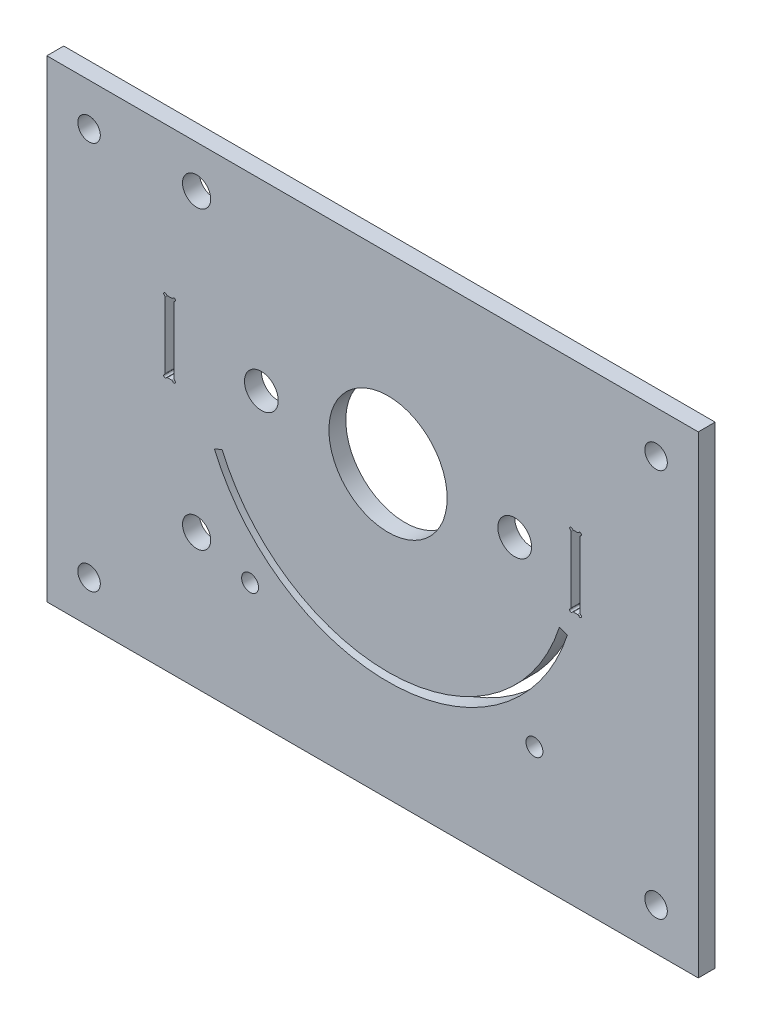
SolidWorks part; units mm, degrees
ref_plane "Front Plane" through (0, 0, 0) normal (0, 0, 1) x (1, 0, 0)
ref_plane "Top Plane" through (0, 0, 0) normal (0, 1, 0) x (1, 0, 0)
ref_plane "Right Plane" through (0, 0, 0) normal (1, 0, 0) x (0, 0, -1)
sketch "Sketch2" plane through (0, 0, 0) normal (0, 0, 1) x (1, 0, 0)
  line L12 (0, 0) -> (0, -103) construction
  line L13 (0, 50) -> (-68, 50) construction
  line L23 (0, 0) -> (0, 50) construction
  line L24 (0, 0) -> (-76, 0) construction
  line L25 (-76, -12.6) -> (-76, 12.6)
  line L26 (-76, 12.6) -> (-79.2, 12.6)
  line L27 (-79.2, 12.6) -> (-79.2, -12.6)
  line L28 (-79.2, -12.6) -> (-76, -12.6)
  line L29 (-68, 50) -> (-68, 65) construction
  line L30 (-79.2, 0) -> (-106.2, 0) construction
  line L31 (-106.2, 0) -> (-106.2, 50) construction
  line L33 (-68, 65) -> (95.2, 65)
  line L41 (0, 0) -> (60, 0) construction
  line L42 (60, 0) -> (65, 0) construction
  line L43 (65, -12.6) -> (65, 12.6)
  line L44 (65, 12.6) -> (68.2, 12.6)
  line L45 (68.2, 12.6) -> (68.2, -12.6)
  line L46 (65, -12.6) -> (68.2, -12.6)
  line L47 (68.2, 0) -> (95.2, 0) construction
  line L48 (95.2, 0) -> (95.2, 50) construction
  line L54 (-68, 50) -> (-68, -55) construction
  line L59 (95.2, 65) -> (110.2, 65)
  line L62 (0, -103) -> (110.2, -103)
  line L63 (110.2, 65) -> (110.2, -103)
  line L64 (-68, 65) -> (-106.2, 65)
  line L65 (-106.2, 65) -> (-121.2, 65)
  line L66 (-121.2, 65) -> (-121.2, -103)
  line L67 (0, -103) -> (-121.2, -103)
  circle A7 centre (0, 0) radius 21
  circle A8 centre (-68, 50) radius 5 construction
  circle A9 centre (-68, -55) radius 5 construction
  point P9 (-76, 0)
  point P13 (0, -103)
  point P25 (65, 0)
  dimension "D1" = 42
  dimension "D4" = 10
  dimension "D10" = 27
  dimension "D11" = 15
  dimension "D12" = 15
  dimension "D26" = 10
  dimension "D2" = 103
  dimension "D3" = 68
  dimension "D5" = 76
  dimension "D6" = 50
  dimension "D7" = 25.2
  dimension "D8" = 3.2
  dimension "D9" = 15
  dimension "D14" = 60
  dimension "D15" = 5
  dimension "D16" = 25.2
  dimension "D17" = 3.2
  dimension "D18" = 27
  dimension "D19" = 50
  dimension "D20" = 50
  dimension "D25" = 105
extrude "Boss-Extrude1" add sketch "Sketch2" along normal mid plane 6
sketch "Sketch6" plane through (0, 0, 0) normal (0, 0, 1) x (1, 0, 0)
  line L0 (-121.2, 65) -> (-106.2, 65) construction
  line L1 (110.2, 65) -> (-121.2, 65) construction
  line L2 (-106.2, 65) -> (-106.2, 50) construction
  line L3 (110.2, 65) -> (95.2, 65) construction
  line L4 (95.2, 65) -> (95.2, 50) construction
  line L5 (110.2, -103) -> (95.2, -103) construction
  line L6 (-121.2, -103) -> (110.2, -103) construction
  line L7 (95.2, -103) -> (95.2, -88) construction
  line L8 (-121.2, -103) -> (-106.2, -103) construction
  line L9 (-106.2, -103) -> (-106.2, -88) construction
  line L10 (-106.2, 50) -> (-68, 50) construction
  line L11 (-121.2, 65) -> (-121.2, -103) construction
  line L12 (-68, 50) -> (-68, -55) construction
  dimension "D1" = 15
  dimension "D2" = 15
  dimension "D3" = 15
  dimension "D4" = 15
  dimension "D5" = 15
  dimension "D6" = 15
  dimension "D7" = 15
  dimension "D8" = 15
  dimension "D9" = 53.2
  dimension "D10" = 105
hole_wizard "Ø10.0 (10) Diameter Hole1" positions "Sketch11" profile "Sketch12" hole size "Ø10.0" standard "AS" end condition through all
sketch "Sketch11" plane through (0, 0, 3) normal (0, 0, 1) x (1, 0, 0)
  point P0 (-68, 50)
  point P3 (-68, -55)
sketch "Sketch12" plane through (-68, 50, 3) normal (1, 0, 0) x (0, -1, 0)
  line L0 (0, 0) -> (0, 6)
  line L1 (0, 6) -> (5, 6)
  line L2 (5, 6) -> (5, 0)
  line L5 (5, 0) -> (0, 0)
  line L11 (0, -6.35) -> (0, 107.95) construction
  dimension "Thru Hole Dia." = 10
  dimension "Thru Hole Depth" = 6
hole_wizard "Ø8.0 (8) Diameter Hole1" positions "Sketch13" profile "Sketch14" hole size "Ø8.0" standard "AS" end condition through all
sketch "Sketch13" plane through (0, 0, 3) normal (0, 0, 1) x (1, 0, 0)
  point P0 (-106.2, 50)
  point P3 (-106.2, -88)
  point P6 (95.2, -88)
  point P9 (95.2, 50)
sketch "Sketch14" plane through (-106.2, 50, 3) normal (1, 0, 0) x (0, -1, 0)
  line L0 (0, 0) -> (0, 6)
  line L1 (0, 6) -> (4, 6)
  line L2 (4, 6) -> (4, 0)
  line L5 (4, 0) -> (0, 0)
  line L11 (0, -6.35) -> (0, 107.95) construction
  dimension "Thru Hole Dia." = 8
  dimension "Thru Hole Depth" = 6
sketch "Sketch15" plane through (0, 0, -3) normal (0, 0, -1) x (-1, 0, 0)
  line L0 (-45, 0) -> (45, 0) construction
  point P4 (0, 0)
  point P6 (-45, 0)
  point P7 (45, 0)
  dimension "D1" = 90
hole_wizard "Ø12.0 (12) Diameter Hole1" positions "Sketch16" profile "Sketch17" hole size "Ø12.0" standard "ANSI Metric" end condition through all
sketch "Sketch16" plane through (0, 0, -3) normal (0, 0, -1) x (-1, 0, 0)
  point P0 (-45, 0)
  point P3 (45, 0)
sketch "Sketch17" plane through (45, 0, -3) normal (1, 0, 0) x (0, 1, 0)
  line L0 (0, 0) -> (0, 6)
  line L1 (0, 6) -> (6, 6)
  line L2 (6, 6) -> (6, 0)
  line L5 (6, 0) -> (0, 0)
  line L11 (0, -6.35) -> (0, 107.95) construction
  dimension "Thru Hole Dia." = 12
  dimension "Thru Hole Depth" = 6
sketch "Sketch18" plane through (0, 0, 3) normal (0, 0, 1) x (1, 0, 0)
  line L0 (0, 0) -> (0, -147.0901) construction
  line L1 (-58.9123, -25.0068) -> (-61.6738, -26.179)
  line L2 (60.8676, -19.7771) -> (63.7208, -20.7041)
  arc A1 (-61.6738, -26.179) -> (63.7208, -20.7041) centre (0, 0) ccw
  arc A2 (-58.9123, -25.0068) -> (60.8676, -19.7771) centre (0, 0) ccw
  dimension "D1" = 134
  dimension "D2" = 3
  dimension "D3" = 67
  dimension "D4" = 72
extrude "Cut-Extrude1" cut sketch "Sketch18" against normal through all both and the other way through all
sketch "Sketch20" plane through (0, 0, -3) normal (0, 0, -1) x (-1, 0, 0)
  line L0 (0, 0) -> (-52, -61) construction
  line L1 (0, 0) -> (49, -61) construction
  line L2 (0, 0) -> (0, -161.413) construction
  line L3 (79.2, 12.6) -> (79.2, -12.6) construction
  line L4 (76, 12.6) -> (79.2, 12.6) construction
  circle A1 centre (0, 0) radius 21 construction
  point P6 (-52, -61)
  point P9 (49, -61)
  dimension "D3" = 42
  dimension "D6" = 79.2
  dimension "D1" = 61
  dimension "D2" = 40.446
  dimension "D4" = 38.774
  dimension "D5" = 61
  dimension "D7" = 12.6
hole_wizard "Ø6.0 (6) Diameter Hole2" positions "Sketch25" profile "Sketch26" hole size "Ø6.0" standard "AS" end condition through all
sketch "Sketch25" plane through (0, 0, -3) normal (0, 0, -1) x (-1, 0, 0)
  point P0 (49, -61)
  point P3 (-52, -61)
sketch "Sketch26" plane through (-49, -61, -3) normal (1, 0, 0) x (0, 1, 0)
  line L0 (0, 0) -> (0, 6)
  line L1 (0, 6) -> (3, 6)
  line L2 (3, 6) -> (3, 0)
  line L5 (3, 0) -> (0, 0)
  line L11 (0, -6.35) -> (0, 107.95) construction
  dimension "Thru Hole Dia." = 6
  dimension "Thru Hole Depth" = 6
sketch "Sketch27" plane through (0, 0, -3) normal (0, 0, -1) x (-1, 0, 0)
  circle A0 centre (-65, 12.6) radius 0.5
  circle A1 centre (-68.2, 12.6) radius 0.5
  circle A2 centre (-65, -12.6) radius 0.5
  circle A3 centre (-68.2, -12.6) radius 0.5
  circle A4 centre (79.2, 12.6) radius 0.5
  circle A5 centre (76, 12.6) radius 0.5
  circle A6 centre (79.2, -12.6) radius 0.5
  circle A7 centre (76, -12.6) radius 0.5
  dimension "D1" = 1
extrude "Cut-Extrude2" cut sketch "Sketch27" against normal through all
fillet "Fillet1" radius 0.5 16 edges at (-76.5, 12.6, 0) (-76, 12.1, 0) (-79.2, 12.1, 0) (-78.7, 12.6, 0) (-79.2, -12.1, 0) (-78.7, -12.6, 0) (-76.5, -12.6, 0) (-76, -12.1, 0) (68.2, -12.1, 0) (67.7, -12.6, 0) (65.5, -12.6, 0) (65, -12.1, 0) (65, 12.1, 0) (65.5, 12.6, 0) (68.2, 12.1, 0) (67.7, 12.6, 0)
